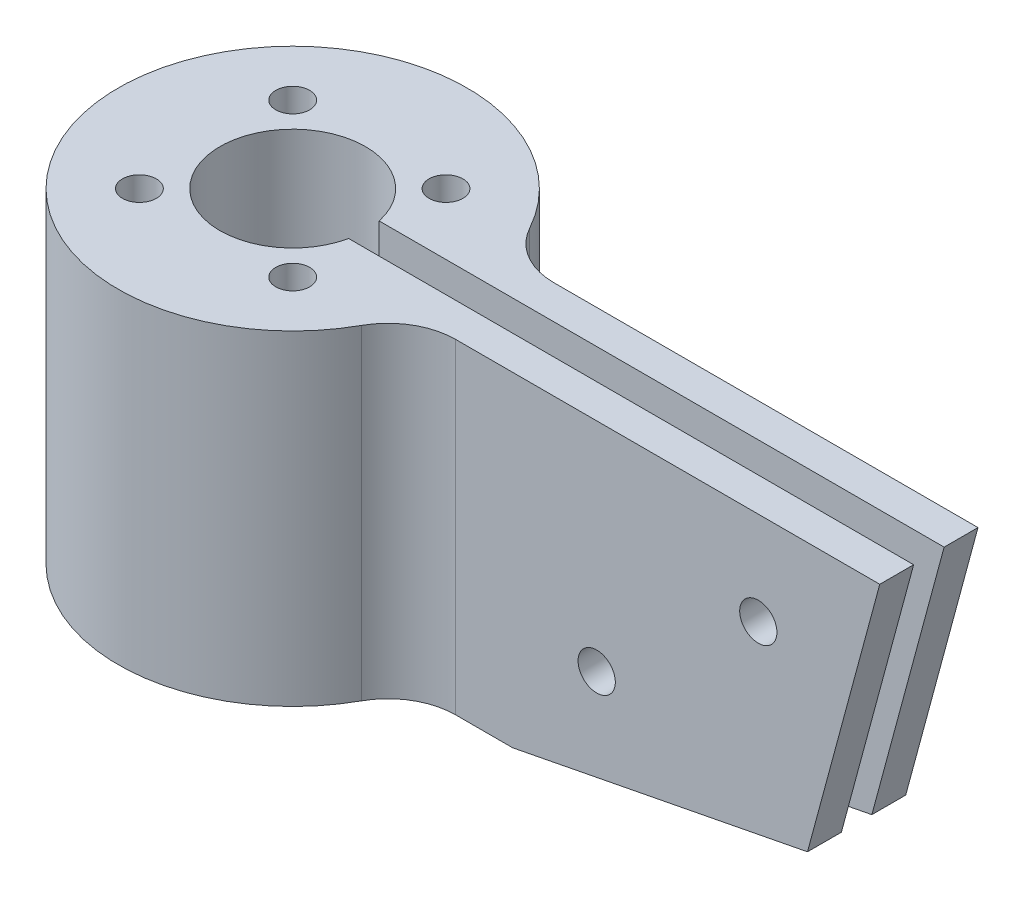
SolidWorks part; units mm, degrees
ref_plane "Front Plane" through (0, 0, 0) normal (0, 0, 1) x (1, 0, 0)
ref_plane "Top Plane" through (0, 0, 0) normal (0, 1, 0) x (1, 0, 0)
ref_plane "Right Plane" through (0, 0, 0) normal (1, 0, 0) x (0, 0, -1)
sketch "Sketch1" plane through (0, 0, 0) normal (0, 1, 0) x (1, 0, 0)
  line L0 (0, 0) -> (39.6935, 0) construction
  line L1 (10.5119, 2.25) -> (39.7083, 2.25)
  line L2 (39.7083, 2.25) -> (39.7083, 7.25)
  line L3 (39.7083, 7.25) -> (24.7083, 7.25)
  line L4 (39.7083, -2.25) -> (39.7083, -7.25)
  line L5 (10.5119, -2.25) -> (39.7083, -2.25)
  line L6 (39.7083, -7.25) -> (24.7083, -7.25)
  arc A0 (10.5119, 2.25) -> (10.5119, -2.25) centre (0, 0) ccw
  arc A2 (24.7083, 7.25) -> (24.7083, -7.25) centre (0, 0) ccw
  dimension "D1" = 21.5
  dimension "D2" = 15
  dimension "D3" = 2.25
  dimension "D4" = 5
  dimension "D5" = 15
extrude "Boss-Extrude1" add sketch "Sketch1" along normal blind 48
fillet "Fillet1" radius 10 2 edges at (24.7083, 24, 7.25) (24.7083, 24, -7.25)
sketch "Sketch5" plane through (0, 48, 0) normal (0, 1, 0) x (1, 0, 0)
  line L0 (0, 0) -> (0, 16) construction
  line L1 (0, 0) -> (-22.6274, 22.6274) construction
  line L2 (0, 0) -> (-24.03, -24.03) construction
  line L3 (0, 0) -> (23.5697, -23.5697) construction
  line L4 (0, 0) -> (24.0916, 24.0916) construction
  circle A1 centre (-11.3137, 11.3137) radius 2.5
  circle A2 centre (-11.3137, -11.3137) radius 2.5
  circle A3 centre (11.3137, -11.3137) radius 2.5
  circle A4 centre (11.3137, 11.3137) radius 2.5
  point P16 (0, 0)
  dimension "D3" = 5
  dimension "D2" = 45
extrude "Cut-Extrude3" cut sketch "Sketch5" against normal blind 10
sketch "Sketch6" plane through (0, 0, 7.25) normal (0, 0, 1) x (1, 0, 0)
  line L0 (39.7083, 0) -> (83.2394, 8.4616)
  line L1 (83.2394, 8.4616) -> (93.9091, 48)
  line L2 (93.9091, 48) -> (39.7083, 48)
  line L3 (39.7083, 48) -> (39.7083, 0)
  line L4 (31.3129, 0) -> (39.7083, 0) construction
  dimension "D1" = 169
extrude "Boss-Extrude2" add sketch "Sketch6" against normal up to surface (5 mm away) up to face at (25.1101, 24, 2.25)
sketch "Sketch7" plane through (0, 0, -7.25) normal (0, 0, -1) x (-1, 0, 0)
  line L4 (-39.7083, 0) -> (-31.3129, 0)
  line L5 (-31.3129, 0) -> (-31.3129, 48)
  line L6 (-31.3129, 48) -> (-39.7083, 48)
  line L7 (-39.7083, 48) -> (-39.7083, 0)
  line L8 (-39.7083, 0) -> (-31.3129, 0)
  line L9 (-31.3129, 0) -> (-31.3129, 48)
  line L10 (-31.3129, 48) -> (-39.7083, 48)
  line L13 (-31.3129, 48) -> (-93.9091, 48)
  line L14 (-31.3129, 0) -> (-31.3129, 48)
  line L15 (-39.7083, 0) -> (-31.3129, 0)
  line L16 (-83.2394, 8.4616) -> (-39.7083, 0)
  line L17 (-93.9091, 48) -> (-83.2394, 8.4616)
  line L18 (-31.3129, 48) -> (-93.9091, 48)
  line L19 (-31.3129, 0) -> (-31.3129, 48)
  line L20 (-39.7083, 0) -> (-31.3129, 0)
  line L21 (-83.2394, 8.4616) -> (-39.7083, 0)
  line L22 (-93.9091, 48) -> (-83.2394, 8.4616)
  line M15 (-39.7083, 48) -> (-39.7083, 0)
  dimension "D1" = 0
  dimension "D2" = 0
extrude "Boss-Extrude3" add sketch "Sketch7" against normal blind 5 contours L18 L22 L21 M15
sketch "Sketch8" plane through (0, 0, -7.25) normal (0, 0, -1) x (-1, 0, 0)
  line L0 (-93.9091, 48) -> (-31.3129, 0) construction
  circle A0 centre (-75.9781, 34.2501) radius 2.75
  circle A1 centre (-52.1237, 15.9581) radius 2.75
  dimension "D1" = 5.5
  dimension "D2" = 5.5
extrude "Cut-Extrude4" cut sketch "Sketch8" against normal blind 27
